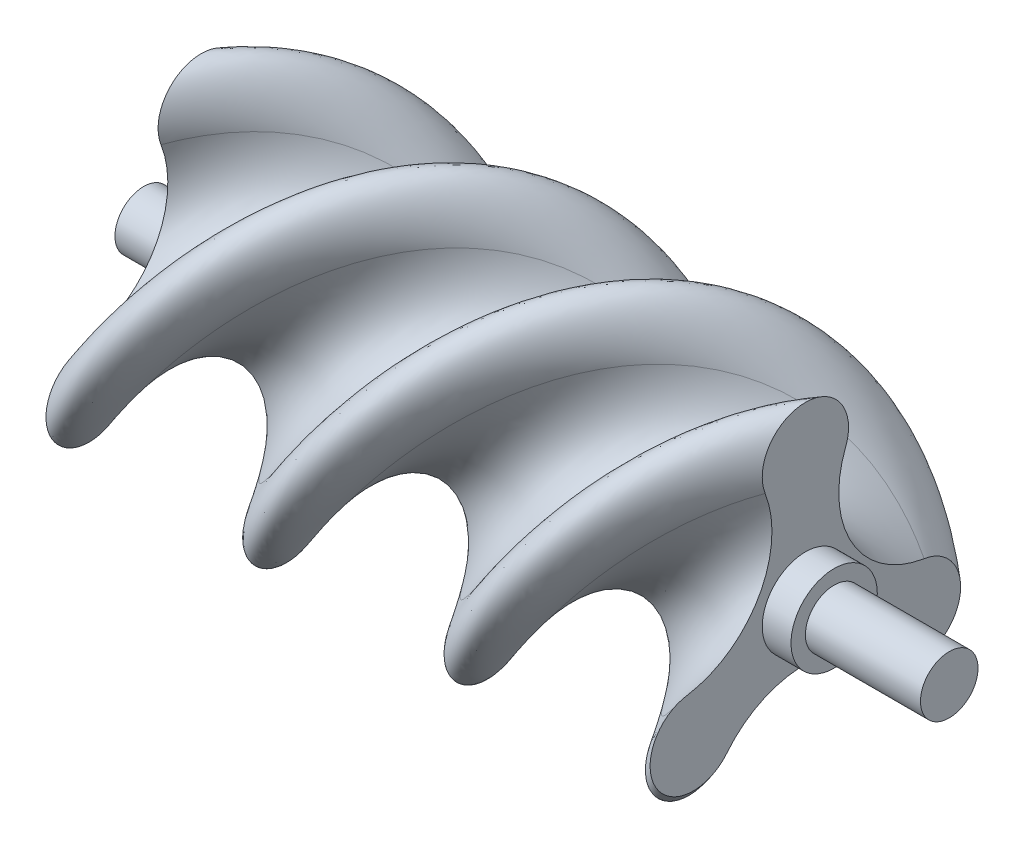
SolidWorks part; units mm, degrees
material "Cast Alloy Steel"
ref_plane "Front Plane" through (0, 0, 0) normal (0, 0, 1) x (1, 0, 0)
ref_plane "Top Plane" through (0, 0, 0) normal (0, 1, 0) x (1, 0, 0)
ref_plane "Right Plane" through (0, 0, 0) normal (1, 0, 0) x (0, 0, -1)
sketch "Sketch1" plane through (0, 0, 0) normal (1, 0, 0) x (0, 0, -1)
  line L0 (0, 0) -> (0, 60) construction
  line L1 (0, 0) -> (51.9615, -30) construction
  line L2 (0, 0) -> (-51.9615, -30) construction
  circle A0 centre (0, 0) radius 60 construction
  circle A1 centre (0, 0) radius 45 construction
  arc A2 (13.9841, 39.5737) -> (-13.9841, 39.5737) centre (0, 45) ccw
  arc A3 (27.2798, -31.8975) -> (41.2639, -7.6763) centre (38.9711, -22.5) ccw
  arc A4 (-41.2639, -7.6763) -> (-27.2798, -31.8975) centre (-38.9711, -22.5) ccw
  arc A5 (-13.9841, 39.5737) -> (-41.2639, -7.6763) centre (-46.6137, 26.9125) cw
  arc A6 (13.9841, 39.5737) -> (41.2639, -7.6763) centre (46.6137, 26.9125) ccw
  arc A7 (-27.2798, -31.8975) -> (27.2798, -31.8975) centre (0, -53.8249) cw
  dimension "D1" = 120
  dimension "D2" = 90
  dimension "D5" = 35
  dimension "D3" = 120
  dimension "D4" = 120
sketch "Sketch2" plane through (0, 0, 0) normal (1, 0, 0) x (0, 0, -1)
  circle A0 centre (0, 0) radius 60
  dimension "D1" = 120
curve "Helix/Spiral1" pitch 210 height 210 turns 1
sweep "Sweep1" add profiles "Sketch1" path "Helix/Spiral1"
sketch "Sketch3" plane through (210, 0, 0) normal (1, 0, 0) x (0, 0, -1)
  circle A0 centre (0, 0) radius 10
  dimension "D1" = 20
extrude "Boss-Extrude1" add sketch "Sketch3" along normal blind 50 and the other way blind 230
sketch "Sketch4" plane through (210, 0, 0) normal (1, 0, 0) x (0, 0, -1)
  circle A0 centre (0, 0) radius 15
  dimension "D1" = 30
extrude "Boss-Extrude2" add sketch "Sketch4" along normal blind 10
sketch "Sketch5" plane through (220, 0, 0) normal (1, 0, 0) x (0, 0, -1)
  line L0 (6.0665, 2.0487) -> (12.6444, -0.3455)
  line L1 (12.6444, -0.3455) -> (9.9082, -7.863)
  line L2 (9.9082, -7.863) -> (3.3304, -5.4689)
  line L3 (3.3304, -5.4689) -> (6.0665, 2.0487)
  line L4 (0, 0) -> (0, 20.8106) construction
  line L5 (0, 0) -> (11.2763, -4.1042) construction
  dimension "D1" = 110
  dimension "D2" = 12
  dimension "D3" = 8
  dimension "D4" = 7
extrude "Boss-Extrude3" add sketch "Sketch5" along normal blind 10
